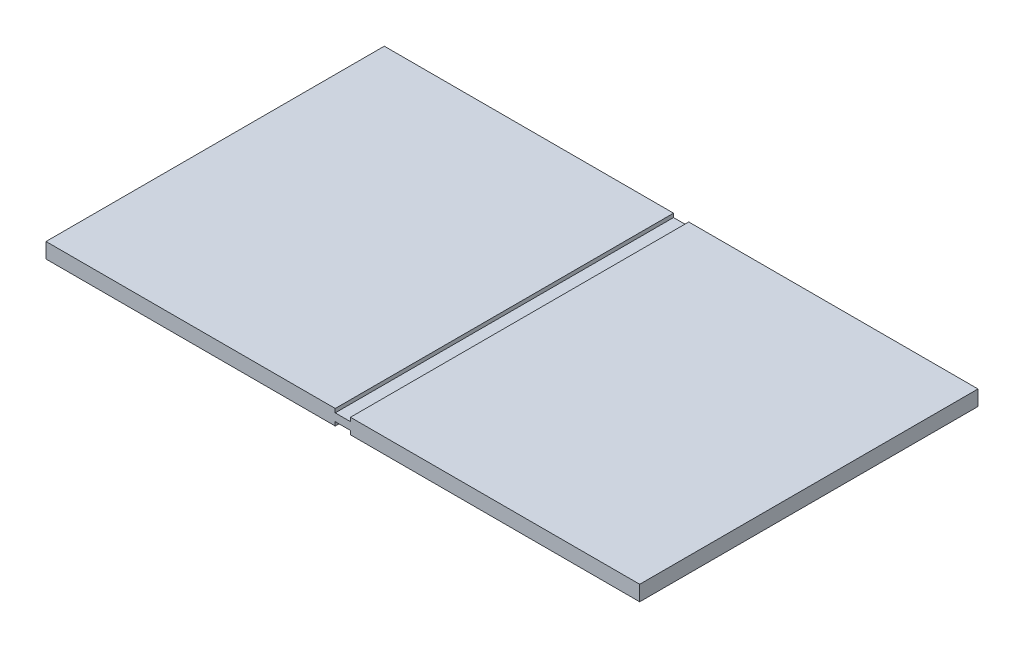
SolidWorks part; units mm, degrees
ref_plane "Front" through (0, 0, 0) normal (0, 0, 1) x (1, 0, 0)
ref_plane "Top" through (0, 0, 0) normal (0, 1, 0) x (1, 0, 0)
ref_plane "Right" through (0, 0, 0) normal (1, 0, 0) x (0, 0, -1)
sketch "Sketch1" plane through (0, 0, 0) normal (0, 1, 0) x (1, 0, 0)
  line L1 (-351, -200) -> (351, -200)
  line L2 (-351, -200) -> (-351, 200)
  line L3 (-351, 200) -> (351, 200)
  line L4 (351, -200) -> (351, 200)
  line L5 (-351, -200) -> (351, 200) construction
  line L6 (-351, 200) -> (351, -200) construction
  point P0 (0, 0)
  dimension "D1" = 702
  dimension "D2" = 400
extrude "Boss-Extrude1" add sketch "Sketch1" along normal blind 18
sketch "Sketch2" plane through (0, 18, 0) normal (0, 1, 0) x (1, 0, 0)
  line L0 (351, 200) -> (-351, 200) construction
  line L1 (9, -200) -> (-9, -200)
  line L2 (9, -200) -> (9, 200)
  line L3 (9, 200) -> (-9, 200)
  line L4 (-9, -200) -> (-9, 200)
  line L5 (9, -200) -> (-9, 200) construction
  line L6 (9, 200) -> (-9, -200) construction
  point P0 (0, 0)
  dimension "D1" = 18
extrude "Cut-Extrude1" cut sketch "Sketch2" against normal blind 4.5
sketch "Sketch3" plane through (0, 0, 0) normal (0, -1, 0) x (-1, 0, 0)
  line L0 (351, -200) -> (-351, -200) construction
  line L1 (9, 200) -> (-9, 200)
  line L2 (9, 200) -> (9, -200)
  line L3 (9, -200) -> (-9, -200)
  line L4 (-9, 200) -> (-9, -200)
  line L5 (9, 200) -> (-9, -200) construction
  line L6 (9, -200) -> (-9, 200) construction
  point P0 (0, 0)
  dimension "D1" = 18
extrude "Cut-Extrude2" cut sketch "Sketch3" against normal blind 4.5
